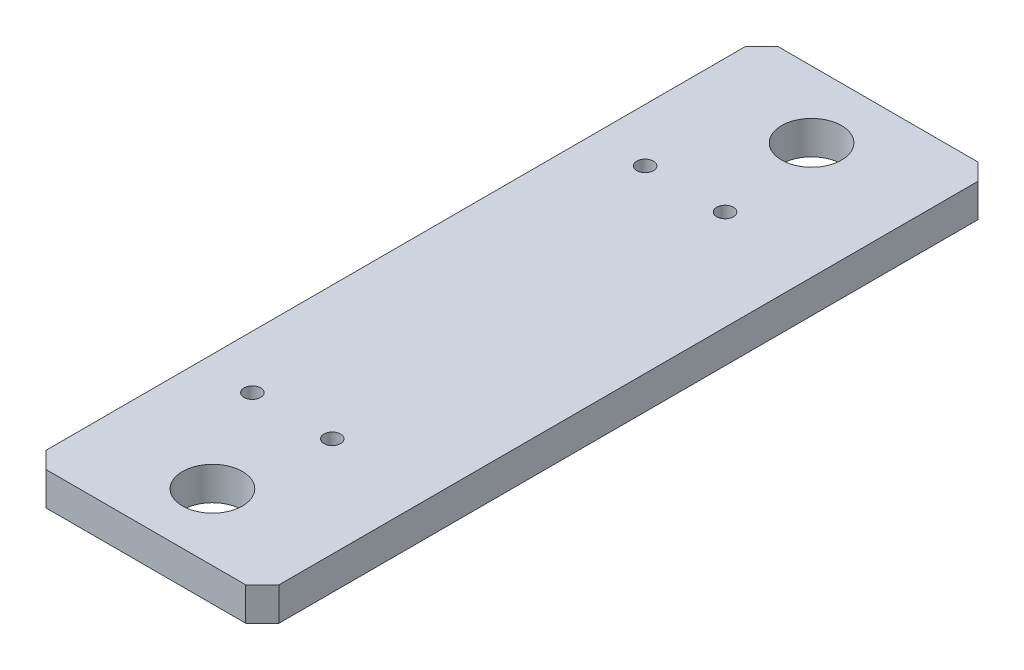
SolidWorks part; units mm, degrees
ref_plane "前基準面" through (0, 0, 0) normal (0, 0, 1) x (1, 0, 0)
ref_plane "上基準面" through (0, 0, 0) normal (0, 1, 0) x (1, 0, 0)
ref_plane "右基準面" through (0, 0, 0) normal (1, 0, 0) x (0, 0, -1)
sketch "草圖1" plane through (0, 0, 0) normal (0, 1, 0) x (1, 0, 0)
  line L0 (0, 80.0469) -> (0, 0) construction
  line L1 (-35, 110) -> (35, 110)
  line L2 (-35, 110) -> (-35, -110)
  line L3 (-35, -110) -> (35, -110)
  line L4 (35, 110) -> (35, -110)
  line L5 (0, 0) -> (44.3499, 0) construction
  dimension "D1" = 35
  dimension "D2" = 220
  dimension "D3" = 70
extrude "伸長1" add sketch "草圖1" along normal blind 10
hole_wizard "M6 螺紋孔1" positions "草圖3" profile "草圖2" tap size "M6" standard "GB" end condition up to next
sketch "草圖3" plane through (0, 10, 0) normal (0, 1, 0) x (-1, 0, 0)
  line L0 (35, 0) -> (25.4541, 0) construction
  line L1 (35, -110) -> (35, 110) construction
  point P0 (19, -59)
  point P1 (19, 59)
  point P3 (-5, -59)
  point P5 (-5, 59)
  dimension "D1" = 16
  dimension "D2" = 24
  dimension "D3" = 118
sketch "草圖2" plane through (-19, 10, -59) normal (1, 0, 0) x (0, 0, 1)
  line L0 (0, 0) -> (0, 10)
  line L1 (0, 10) -> (2.5, 10)
  line L2 (2.5, 10) -> (2.5, 0)
  line L5 (2.5, 0) -> (0, 0)
  line L11 (0, -6.35) -> (0, 107.95) construction
  dimension "貫穿螺孔鑽直徑" = 5
  dimension "貫穿螺孔鑽深度" = 10
cosmetic thread "鑽孔螺紋1" parameters "D2"=6
cosmetic thread "鑽孔螺紋2" parameters "D2"=6
cosmetic thread "鑽孔螺紋3" parameters "D2"=6
cosmetic thread "鑽孔螺紋4" parameters "D2"=6
hole_wizard "Ø18.0 (18) 直徑孔1" positions "草圖5" profile "草圖4" hole size "Ø18.0" standard "ISO" end condition up to next
sketch "草圖5" plane through (0, 10, 0) normal (0, 1, 0) x (-1, 0, 0)
  line L0 (0, -110) -> (0, 0) construction
  line L1 (-35, -110) -> (35, -110) construction
  line L2 (0, 0) -> (-22.118, 0) construction
  point P0 (0, -90)
  point P1 (0, 90)
  dimension "D1" = 180
sketch "草圖4" plane through (0, 10, -90) normal (1, 0, 0) x (0, 0, 1)
  line L0 (0, 0) -> (0, 10)
  line L1 (0, 10) -> (9, 10)
  line L2 (9, 10) -> (9, 0)
  line L5 (9, 0) -> (0, 0)
  line L11 (0, -6.35) -> (0, 107.95) construction
  dimension "貫穿孔直徑" = 18
  dimension "貫穿孔深度" = 10
chamfer "導角1" distance 5 angle 45 4 edges at (-35, 5, -110) (35, 5, -110) (-35, 5, 110) (35, 5, 110)
